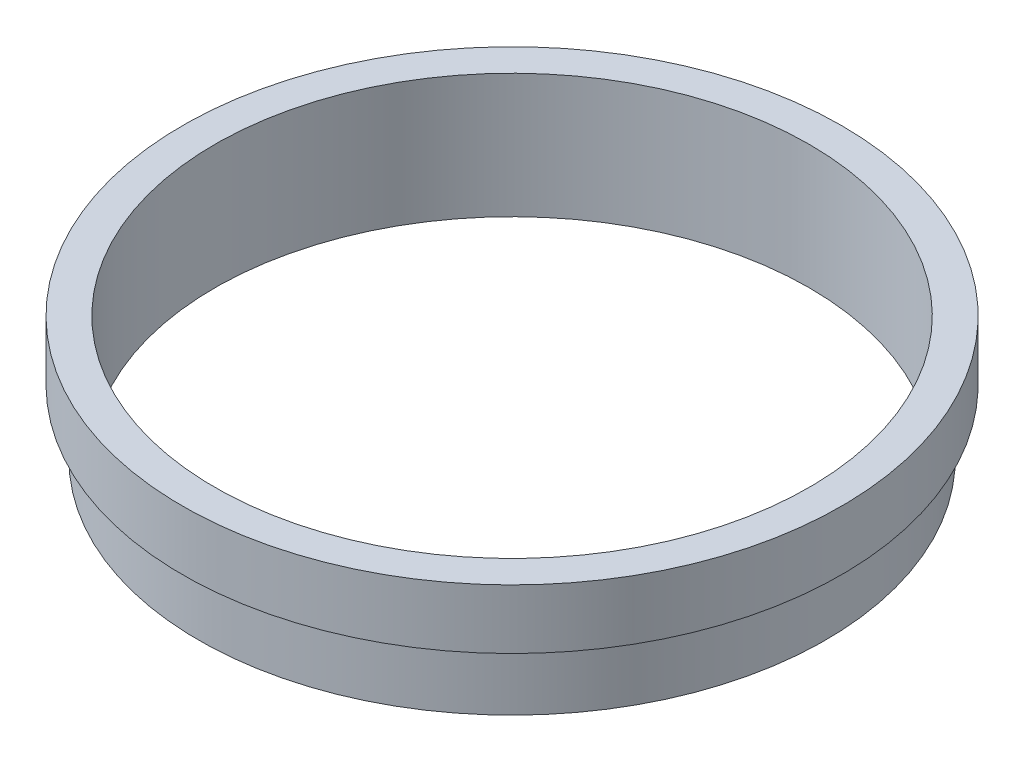
SolidWorks part; units mm, degrees
ref_plane "Front Plane" through (0, 0, 0) normal (0, 0, 1) x (1, 0, 0)
ref_plane "Top Plane" through (0, 0, 0) normal (0, 1, 0) x (1, 0, 0)
ref_plane "Right Plane" through (0, 0, 0) normal (1, 0, 0) x (0, 0, -1)
sketch "Sketch1" plane through (0, 0, 0) normal (0, 0, 1) x (1, 0, 0)
  line L0 (0, 0) -> (0, 20)
  line L2 (27.5, 0) -> (29, 0)
  line L3 (27.5, 0) -> (27.5, 11.5)
  line L4 (27.5, 11.5) -> (29, 11.5)
  line L5 (29, 0) -> (29, 11.5)
  line L6 (29, 11.5) -> (30.5, 11.5)
  line L7 (29, 11.5) -> (29, 6)
  line L8 (29, 6) -> (30.5, 6)
  line L9 (30.5, 11.5) -> (30.5, 6)
  dimension "D1" = 11.5
  dimension "D2" = 27.5
  dimension "D3" = 1.5
  dimension "D4" = 1.5
  dimension "D5" = 5.5
revolve "Revolve1" add sketch "Sketch1" angle 360 about L0
